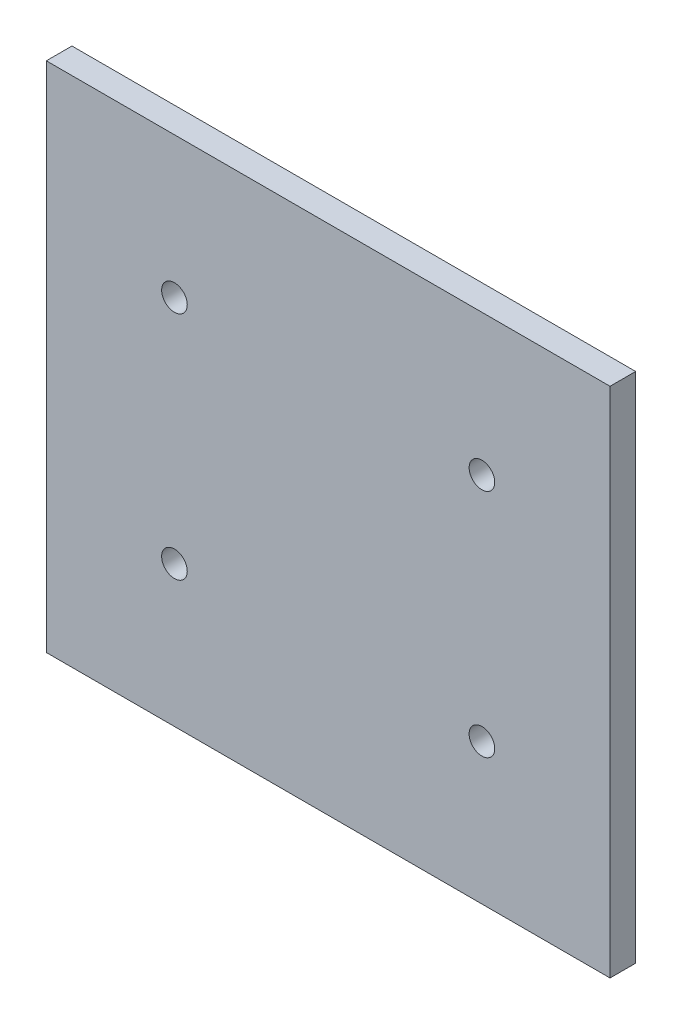
SolidWorks part; units mm, degrees
ref_plane "Front Plane" through (0, 0, 0) normal (0, 0, 1) x (1, 0, 0)
ref_plane "Top Plane" through (0, 0, 0) normal (0, 1, 0) x (1, 0, 0)
ref_plane "Right Plane" through (0, 0, 0) normal (1, 0, 0) x (0, 0, -1)
sketch "Sketch1" plane through (0, 0, 0) normal (0, 0, 1) x (1, 0, 0)
  line L0 (19.05, 46.0375) -> (19.05, 0) construction
  line L1 (0, 0) -> (38.1, 0) construction
  line L2 (0, 0) -> (0, 28.575) construction
  line L3 (0, 28.575) -> (38.1, 28.575) construction
  line L4 (38.1, 0) -> (38.1, 28.575) construction
  line L5 (-15.875, 46.0375) -> (53.975, 46.0375)
  line L6 (-15.875, 46.0375) -> (-15.875, -17.4625)
  line L7 (-15.875, -17.4625) -> (53.975, -17.4625)
  line L8 (53.975, 46.0375) -> (53.975, -17.4625)
  line L9 (-15.875, 14.2875) -> (0, 14.2875) construction
  circle A0 centre (0, 28.575) radius 1.5875
  circle A1 centre (38.1, 28.575) radius 1.5875
  circle A2 centre (38.1, 0) radius 1.5875
  circle A3 centre (0, 0) radius 1.5875
  dimension "D5" = 3.175
  dimension "D1" = 28.575
  dimension "D2" = 38.1
  dimension "D3" = 69.85
  dimension "D4" = 63.5
extrude "Boss-Extrude1" add sketch "Sketch1" along normal blind 3.175
